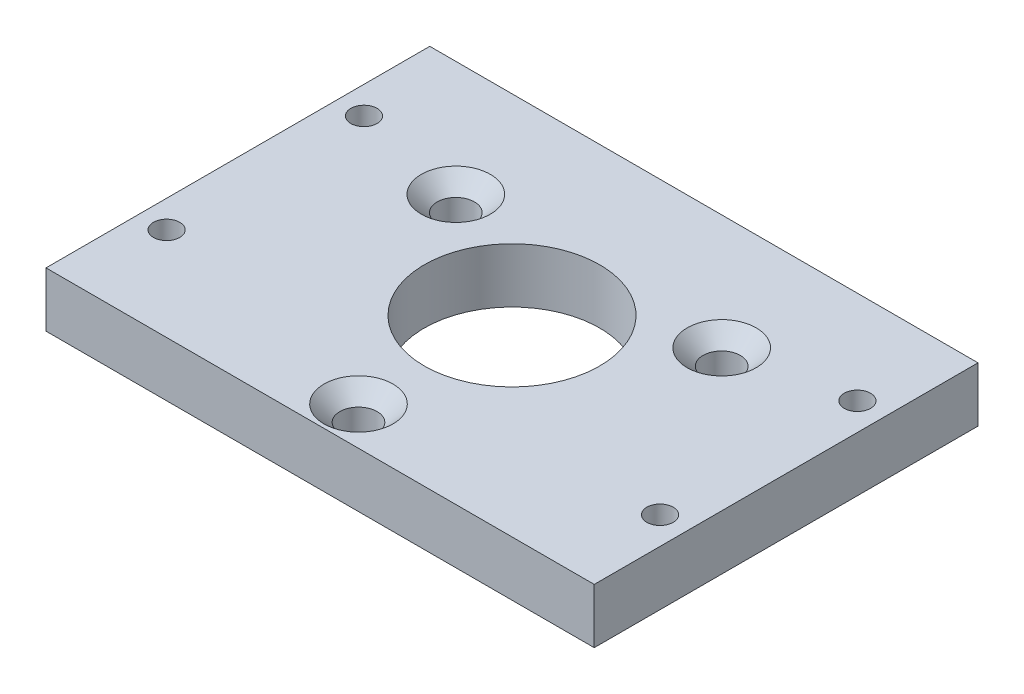
SolidWorks part; units mm, degrees
ref_plane "Front Plane" through (0, 0, 0) normal (0, 0, 1) x (1, 0, 0)
ref_plane "Top Plane" through (0, 0, 0) normal (0, 1, 0) x (1, 0, 0)
ref_plane "Right Plane" through (0, 0, 0) normal (1, 0, 0) x (0, 0, -1)
sketch "Sketch1" plane through (0, 0, 0) normal (0, 1, 0) x (1, 0, 0)
  line L1 (25, -17.5) -> (-25, -17.5)
  line L2 (25, -17.5) -> (25, 17.5)
  line L3 (25, 17.5) -> (-25, 17.5)
  line L4 (-25, -17.5) -> (-25, 17.5)
  line L5 (25, -17.5) -> (-25, 17.5) construction
  line L6 (25, 17.5) -> (-25, -17.5) construction
  circle A0 centre (0, 0) radius 8
  point P0 (0, 0)
  dimension "D1" = 35
  dimension "D2" = 50
extrude "Boss-Extrude1" add sketch "Sketch1" along normal blind 5
sketch "Sketch2" plane through (0, 5, 0) normal (0, 1, 0) x (1, 0, 0)
  line L0 (0, 0) -> (17.9804, 0) construction
  line L1 (0, 0) -> (12.1244, 7)
  line L2 (-22.5, -17.5) -> (-22.5, 17.5) construction
  line L3 (-25, -17.5) -> (25, -17.5) construction
  line L4 (25, 17.5) -> (-25, 17.5) construction
  line L5 (0, -17.5) -> (0, 17.5) construction
  line L6 (0, 0) -> (-25, 0) construction
  line L7 (-25, 17.5) -> (-25, -17.5) construction
  circle A0 centre (0, 0) radius 14
  circle A1 centre (12.1244, 7) radius 1.5
  circle A2 centre (0, -14) radius 1.5
  circle A3 centre (-12.1244, 7) radius 1.5
  circle A4 centre (-22.5, -9) radius 1
  circle A5 centre (-22.5, 9) radius 1
  circle A6 centre (22.5, 9) radius 1
  circle A7 centre (22.5, -9) radius 1
  point P13 (0, 0)
  dimension "D1" = 30
  dimension "D4" = 9
  dimension "D5" = 9
  dimension "D3" = 22.5
  dimension "D2" = 3
hole_wizard "CSK for M3 Countersunk Flat Head Screw1" positions "Sketch3" profile "Sketch4" countersink size "M3" standard "ISO" end condition through all
sketch "Sketch3" plane through (0, 5, 0) normal (0, 1, 0) x (1, 0, 0)
  point P0 (12.1244, 7)
  point P3 (0, -14)
  point P6 (-12.1244, 7)
sketch "Sketch4" plane through (12.1244, 5, -7) normal (1, 0, 0) x (0, 0, 1)
  line L0 (0, 0) -> (0, 5)
  line L1 (0, 5) -> (1.7, 5)
  line L2 (1.7, 5) -> (1.7, 1.45)
  line L3 (1.7, 1.45) -> (3.15, 0)
  line L5 (3.15, 0) -> (0, 0)
  line L6 (-1.7, 1.45) -> (-3.15, 0) construction
  line L11 (0, -6.35) -> (0, 107.95) construction
  dimension "Thru Hole Dia." = 3.4
  dimension "Thru Hole Depth" = 5
  dimension "Near C'Sink Dia." = 6.3
  dimension "Near C'Sink Angle" = 90
hole_wizard "CSK for M2 Countersunk Flat Head Screw1" positions "Sketch5" profile "Sketch6" countersink size "M2" standard "ISO" end condition through all
sketch "Sketch5" plane through (0, 0, 0) normal (0, -1, 0) x (-1, 0, 0)
  point P0 (22.5, -9)
  point P3 (22.5, 9)
  point P6 (-22.5, 9)
  point P9 (-22.5, -9)
sketch "Sketch6" plane through (-22.5, 0, 9) normal (1, 0, 0) x (0, 0, -1)
  line L0 (0, 0) -> (0, 5)
  line L1 (0, 5) -> (1.2, 5)
  line L2 (1.2, 5) -> (1.2, 1)
  line L3 (1.2, 1) -> (2.2, 0)
  line L5 (2.2, 0) -> (0, 0)
  line L6 (-1.2, 1) -> (-2.2, 0) construction
  line L11 (0, -6.35) -> (0, 107.95) construction
  dimension "Thru Hole Dia." = 2.4
  dimension "Thru Hole Depth" = 5
  dimension "Near C'Sink Dia." = 4.4
  dimension "Near C'Sink Angle" = 90
